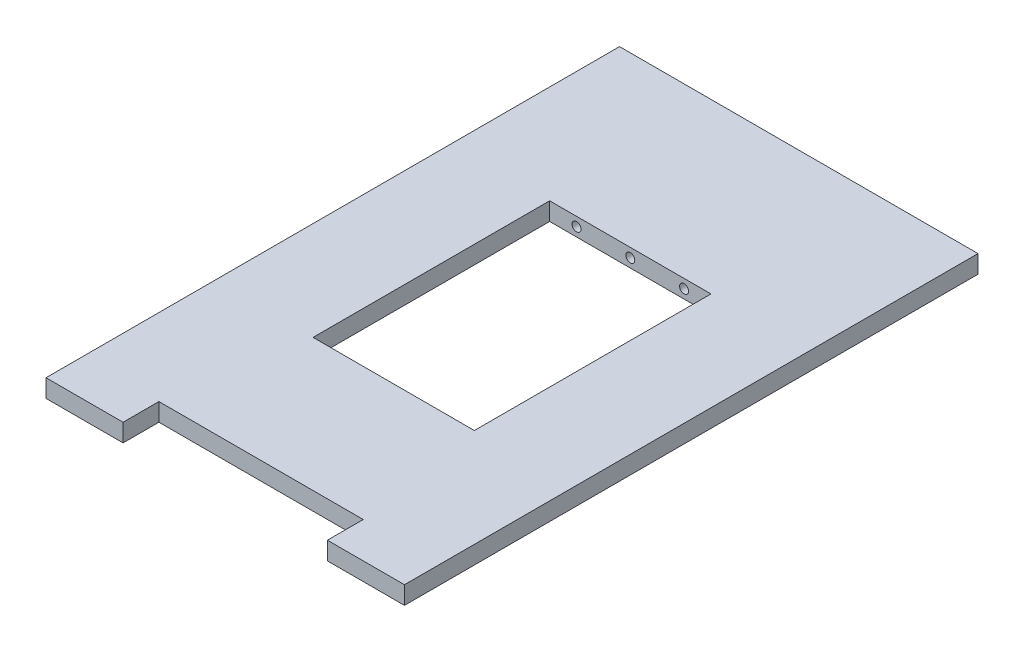
SolidWorks part; units mm, degrees
material "Mahogany"
ref_plane "Front Plane" through (0, 0, 0) normal (0, 0, 1) x (1, 0, 0)
ref_plane "Top Plane" through (0, 0, 0) normal (0, 1, 0) x (1, 0, 0)
ref_plane "Right Plane" through (0, 0, 0) normal (1, 0, 0) x (0, 0, -1)
sketch "Sketch1" plane through (0, 0, 0) normal (0, 1, 0) x (1, 0, 0)
  line L1 (-50, -80) -> (50, -80)
  line L2 (-50, -80) -> (-50, 80)
  line L3 (-50, 80) -> (50, 80)
  line L4 (50, -80) -> (50, 80)
  line L5 (-50, -80) -> (50, 80) construction
  line L6 (-50, 80) -> (50, -80) construction
  point P0 (0, 0)
  dimension "D1" = 160
  dimension "D2" = 100
extrude "Boss-Extrude1" add sketch "Sketch1" along normal blind 5
sketch "Sketch2" plane through (0, 5, 0) normal (0, 1, 0) x (1, 0, 0)
  line L1 (-22.5, -33) -> (22.5, -33)
  line L2 (-22.5, -33) -> (-22.5, 33)
  line L3 (-22.5, 33) -> (22.5, 33)
  line L4 (22.5, -33) -> (22.5, 33)
  line L5 (-22.5, -33) -> (22.5, 33) construction
  line L6 (-22.5, 33) -> (22.5, -33) construction
  point P0 (0, 0)
  dimension "D1" = 45
  dimension "D2" = 66
extrude "Cut-Extrude1" cut sketch "Sketch2" against normal through all
hole_wizard "Ø2.5mm Dowel Hole1" positions "Sketch3" profile "Sketch5" hole size "Ø2.5" standard "ANSI Metric"
sketch "Sketch3" plane through (0, 0, -33) normal (0, 0, 1) x (1, 0, 0)
  line L0 (22.5, 0) -> (-22.5, 0) construction
  point P0 (0, 2.5)
  point P2 (15, 2.5)
  point P4 (-15, 2.5)
  point P10 (0, 0)
  dimension "D1" = 2.5
  dimension "D2" = 2.5
  dimension "D3" = 2.5
  dimension "D4" = 15
  dimension "D5" = 15
sketch "Sketch5" plane through (0, 2.5, -33) normal (1, 0, 0) x (0, -1, 0)
  line L0 (0, 0) -> (0, 10.7511)
  line L1 (0, 10.7511) -> (1.25, 10)
  line L2 (1.25, 10) -> (1.25, 0)
  line L5 (1.25, 0) -> (0, 0)
  line L10 (0, 10.7511) -> (-1.25, 10) construction
  line L11 (0, -6.35) -> (0, 107.95) construction
  dimension "Hole Dia." = 2.5
  dimension "Hole Depth" = 10
  dimension "Drill Angle" = 118
hole_wizard "Ø2.5mm Dowel Hole2" positions "Sketch6" profile "Sketch7" hole size "Ø2.5" standard "ANSI Metric"
sketch "Sketch6" plane through (0, 0, 33) normal (0, 0, -1) x (-1, 0, 0)
  line L0 (22.5, 0) -> (-22.5, 0) construction
  point P0 (0, 2.5)
  point P2 (15, 2.5)
  point P4 (-15, 2.5)
  point P12 (0, 0)
  dimension "D1" = 15
  dimension "D2" = 15
  dimension "D3" = 2.5
sketch "Sketch7" plane through (0, 2.5, 33) normal (1, 0, 0) x (0, 1, 0)
  line L0 (0, 0) -> (0, 10.7511)
  line L1 (0, 10.7511) -> (1.25, 10)
  line L2 (1.25, 10) -> (1.25, 0)
  line L5 (1.25, 0) -> (0, 0)
  line L10 (0, 10.7511) -> (-1.25, 10) construction
  line L11 (0, -6.35) -> (0, 107.95) construction
  dimension "Hole Dia." = 2.5
  dimension "Hole Depth" = 10
  dimension "Drill Angle" = 118
sketch "Sketch8" plane through (0, 5, 0) normal (0, 1, 0) x (1, 0, 0)
  line L0 (-50, -80) -> (50, -80) construction
  line L1 (-28.5, -90) -> (28.5, -90)
  line L2 (-28.5, -90) -> (-28.5, -70)
  line L3 (-28.5, -70) -> (28.5, -70)
  line L4 (28.5, -90) -> (28.5, -70)
  line L5 (-28.5, -90) -> (28.5, -70) construction
  line L6 (-28.5, -70) -> (28.5, -90) construction
  point P0 (0, -80)
  dimension "D1" = 57
  dimension "D2" = 10
extrude "Cut-Extrude2" cut sketch "Sketch8" against normal through all
equation "\"D4\"=15"
